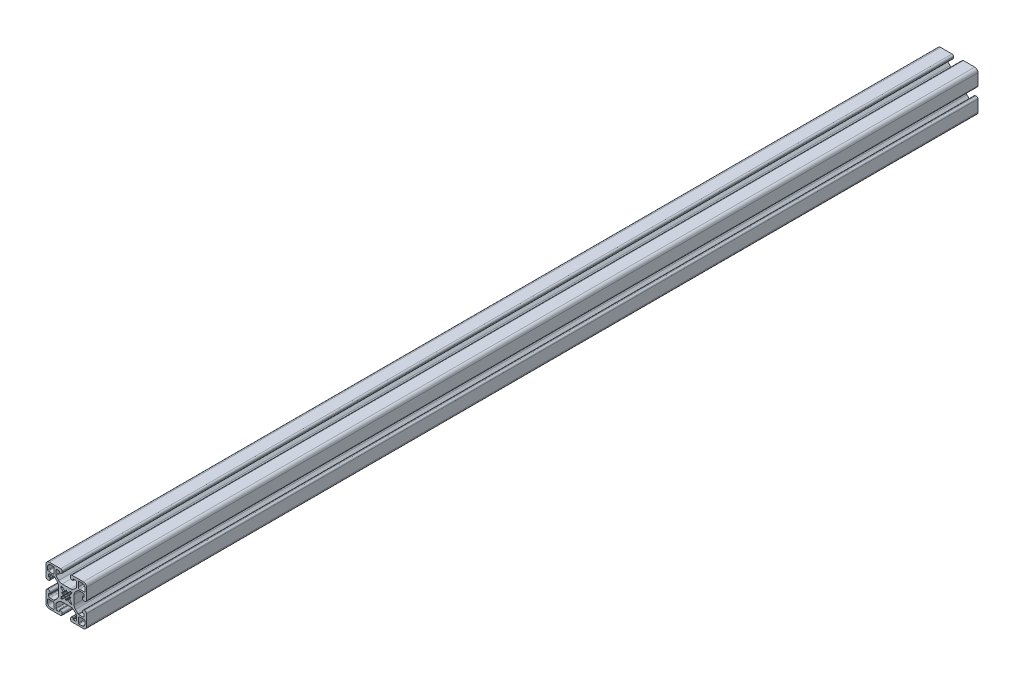
SolidWorks part; units mm, degrees
other "Extrude1"
material "6105-T5 Aluminum"
ref_plane "Front Plane" through (0, 0, 0) normal (0, 0, 1) x (1, 0, 0)
ref_plane "Top Plane" through (0, 0, 0) normal (0, 1, 0) x (1, 0, 0)
ref_plane "Right Plane" through (0, 0, 0) normal (1, 0, 0) x (0, 0, -1)
sketch "Sketch1" plane through (0, 0, 0) normal (0, 0, 1) x (1, 0, 0)
  line L0 (12.4898, -18.345) -> (15.545, -18.345)
  line L1 (11.8598, -13.1298) -> (11.8598, -17.715)
  line L2 (17.715, -11.8598) -> (13.1298, -11.8598)
  line L3 (18.345, -15.545) -> (18.345, -12.4898)
  line L4 (-18.345, -12.4898) -> (-18.345, -15.545)
  line L5 (-13.1298, -11.8598) -> (-17.715, -11.8598)
  line L6 (-11.8598, -17.715) -> (-11.8598, -13.1298)
  line L7 (-15.545, -18.345) -> (-12.4898, -18.345)
  line L8 (18.345, 12.4898) -> (18.345, 15.545)
  line L9 (13.1298, 11.8598) -> (17.715, 11.8598)
  line L10 (11.8598, 17.715) -> (11.8598, 13.1298)
  line L11 (15.545, 18.345) -> (12.4898, 18.345)
  line L12 (-12.4898, 18.345) -> (-15.545, 18.345)
  line L13 (-11.8598, 13.1298) -> (-11.8598, 17.715)
  line L14 (-17.715, 11.8598) -> (-13.1298, 11.8598)
  line L15 (-18.345, 15.545) -> (-18.345, 12.4898)
  line L16 (-5.63, 20) -> (-16.83, 20)
  line L17 (-20, 16.83) -> (-20, 5.63)
  line L18 (-18.43, 4.06) -> (-17.57, 4.06)
  line L19 (-16, 5.63) -> (-16, 6.605)
  line L20 (-16.25, 6.855) -> (-17.25, 6.855)
  line L21 (-17.5, 7.105) -> (-17.5, 9.015)
  line L22 (-16.23, 10.285) -> (-12.2162, 10.285)
  line L23 (-11.5869, 10.0243) -> (-9.0762, 7.5137)
  line L24 (-7.685, 4.1549) -> (-7.685, -4.1549)
  line L25 (-9.0762, -7.5137) -> (-11.5869, -10.0243)
  line L26 (-12.2162, -10.285) -> (-16.23, -10.285)
  line L27 (-17.5, -9.015) -> (-17.5, -7.105)
  line L28 (-17.25, -6.855) -> (-16.25, -6.855)
  line L29 (-16, -6.605) -> (-16, -5.63)
  line L30 (-17.57, -4.06) -> (-18.43, -4.06)
  line L31 (-20, -5.63) -> (-20, -16.83)
  line L32 (-16.83, -20) -> (-5.63, -20)
  line L33 (-4.06, -18.43) -> (-4.06, -17.57)
  line L34 (-5.63, -16) -> (-6.605, -16)
  line L35 (-6.855, -16.25) -> (-6.855, -17.25)
  line L36 (-7.105, -17.5) -> (-9.015, -17.5)
  line L37 (-10.285, -16.23) -> (-10.285, -12.2162)
  line L38 (-10.0243, -11.5869) -> (-7.5137, -9.0762)
  line L39 (-4.1549, -7.685) -> (4.1549, -7.685)
  line L40 (7.5137, -9.0762) -> (10.0243, -11.5869)
  line L41 (10.285, -12.2162) -> (10.285, -16.23)
  line L42 (9.015, -17.5) -> (7.105, -17.5)
  line L43 (6.855, -17.25) -> (6.855, -16.25)
  line L44 (6.605, -16) -> (5.63, -16)
  line L45 (4.06, -17.57) -> (4.06, -18.43)
  line L46 (5.63, -20) -> (16.83, -20)
  line L47 (20, -16.83) -> (20, -5.63)
  line L48 (18.43, -4.06) -> (17.57, -4.06)
  line L49 (16, -5.63) -> (16, -6.605)
  line L50 (16.25, -6.855) -> (17.25, -6.855)
  line L51 (17.5, -7.105) -> (17.5, -9.015)
  line L52 (16.23, -10.285) -> (12.2162, -10.285)
  line L53 (11.5869, -10.0243) -> (9.0762, -7.5137)
  line L54 (7.685, -4.1549) -> (7.685, 4.1549)
  line L55 (9.0762, 7.5137) -> (11.5869, 10.0243)
  line L56 (12.2162, 10.285) -> (16.23, 10.285)
  line L57 (17.5, 9.015) -> (17.5, 7.105)
  line L58 (17.25, 6.855) -> (16.25, 6.855)
  line L59 (16, 6.605) -> (16, 5.63)
  line L60 (17.57, 4.06) -> (18.43, 4.06)
  line L61 (20, 5.63) -> (20, 16.83)
  line L62 (16.83, 20) -> (5.63, 20)
  line L63 (4.06, 18.43) -> (4.06, 17.57)
  line L64 (5.63, 16) -> (6.605, 16)
  line L65 (6.855, 16.25) -> (6.855, 17.25)
  line L66 (7.105, 17.5) -> (9.015, 17.5)
  line L67 (10.285, 16.23) -> (10.285, 12.2162)
  line L68 (10.0243, 11.5869) -> (7.5137, 9.0762)
  line L69 (4.1549, 7.685) -> (-4.1549, 7.685)
  line L70 (-7.5137, 9.0762) -> (-10.0243, 11.5869)
  line L71 (-10.285, 12.2162) -> (-10.285, 16.23)
  line L72 (-9.015, 17.5) -> (-7.105, 17.5)
  line L73 (-6.855, 17.25) -> (-6.855, 16.25)
  line L74 (-6.605, 16) -> (-5.63, 16)
  line L75 (-4.06, 17.57) -> (-4.06, 18.43)
  line L76 (-4.8481, -5.4393) -> (-3.712, -5.1263)
  line L77 (-3.712, -5.1263) -> (-1.5907, -3.0049)
  line L78 (-0.625, -3.3421) -> (-0.4923, -4.0876)
  line L79 (0.4923, -4.0876) -> (0.625, -3.3421)
  line L80 (1.5907, -3.0049) -> (3.712, -5.1263)
  line L81 (3.712, -5.1263) -> (4.8481, -5.4393)
  line L82 (5.4393, -4.8481) -> (5.1263, -3.712)
  line L83 (5.1263, -3.712) -> (3.0049, -1.5907)
  line L84 (3.3421, -0.625) -> (4.0876, -0.4923)
  line L85 (4.0876, 0.4923) -> (3.3421, 0.625)
  line L86 (3.0049, 1.5907) -> (5.1263, 3.712)
  line L87 (5.1263, 3.712) -> (5.4393, 4.8481)
  line L88 (4.8481, 5.4393) -> (3.712, 5.1263)
  line L89 (3.712, 5.1263) -> (1.5907, 3.0049)
  line L90 (0.625, 3.3421) -> (0.4923, 4.0876)
  line L91 (-0.4923, 4.0876) -> (-0.625, 3.3421)
  line L92 (-1.5907, 3.0049) -> (-3.712, 5.1263)
  line L93 (-3.712, 5.1263) -> (-4.8481, 5.4393)
  line L94 (-5.4393, 4.8481) -> (-5.1263, 3.712)
  line L95 (-5.1263, 3.712) -> (-3.0049, 1.5907)
  line L96 (-3.3421, 0.625) -> (-4.0876, 0.4923)
  line L97 (-4.0876, -0.4923) -> (-3.3421, -0.625)
  line L98 (-3.0049, -1.5907) -> (-5.1263, -3.712)
  line L99 (-5.1263, -3.712) -> (-5.4393, -4.8481)
  arc A0 (15.545, -18.345) -> (18.345, -15.545) centre (15.545, -15.545) ccw
  arc A1 (11.8598, -17.715) -> (12.4898, -18.345) centre (12.4898, -17.715) ccw
  arc A2 (13.1298, -11.8598) -> (11.8598, -13.1298) centre (13.1298, -13.1298) ccw
  arc A3 (18.345, -12.4898) -> (17.715, -11.8598) centre (17.715, -12.4898) ccw
  arc A4 (-18.345, -15.545) -> (-15.545, -18.345) centre (-15.545, -15.545) ccw
  arc A5 (-17.715, -11.8598) -> (-18.345, -12.4898) centre (-17.715, -12.4898) ccw
  arc A6 (-11.8598, -13.1298) -> (-13.1298, -11.8598) centre (-13.1298, -13.1298) ccw
  arc A7 (-12.4898, -18.345) -> (-11.8598, -17.715) centre (-12.4898, -17.715) ccw
  arc A8 (18.345, 15.545) -> (15.545, 18.345) centre (15.545, 15.545) ccw
  arc A9 (17.715, 11.8598) -> (18.345, 12.4898) centre (17.715, 12.4898) ccw
  arc A10 (11.8598, 13.1298) -> (13.1298, 11.8598) centre (13.1298, 13.1298) ccw
  arc A11 (12.4898, 18.345) -> (11.8598, 17.715) centre (12.4898, 17.715) ccw
  arc A12 (-15.545, 18.345) -> (-18.345, 15.545) centre (-15.545, 15.545) ccw
  arc A13 (-11.8598, 17.715) -> (-12.4898, 18.345) centre (-12.4898, 17.715) ccw
  arc A14 (-13.1298, 11.8598) -> (-11.8598, 13.1298) centre (-13.1298, 13.1298) ccw
  arc A15 (-18.345, 12.4898) -> (-17.715, 11.8598) centre (-17.715, 12.4898) ccw
  arc A16 (-4.06, 18.43) -> (-5.63, 20) centre (-5.63, 18.43) ccw
  arc A17 (-16.83, 20) -> (-20, 16.83) centre (-16.83, 16.83) ccw
  arc A18 (-20, 5.63) -> (-18.43, 4.06) centre (-18.43, 5.63) ccw
  arc A19 (-17.57, 4.06) -> (-16, 5.63) centre (-17.57, 5.63) ccw
  arc A20 (-16, 6.605) -> (-16.25, 6.855) centre (-16.25, 6.605) ccw
  arc A21 (-17.5, 7.105) -> (-17.25, 6.855) centre (-17.25, 7.105) ccw
  arc A22 (-16.23, 10.285) -> (-17.5, 9.015) centre (-16.23, 9.015) ccw
  arc A23 (-11.5869, 10.0243) -> (-12.2162, 10.285) centre (-12.2162, 9.395) ccw
  arc A24 (-7.685, 4.1549) -> (-9.0762, 7.5137) centre (-12.435, 4.1549) ccw
  arc A25 (-9.0762, -7.5137) -> (-7.685, -4.1549) centre (-12.435, -4.1549) ccw
  arc A26 (-12.2162, -10.285) -> (-11.5869, -10.0243) centre (-12.2162, -9.395) ccw
  arc A27 (-17.5, -9.015) -> (-16.23, -10.285) centre (-16.23, -9.015) ccw
  arc A28 (-17.25, -6.855) -> (-17.5, -7.105) centre (-17.25, -7.105) ccw
  arc A29 (-16.25, -6.855) -> (-16, -6.605) centre (-16.25, -6.605) ccw
  arc A30 (-16, -5.63) -> (-17.57, -4.06) centre (-17.57, -5.63) ccw
  arc A31 (-18.43, -4.06) -> (-20, -5.63) centre (-18.43, -5.63) ccw
  arc A32 (-20, -16.83) -> (-16.83, -20) centre (-16.83, -16.83) ccw
  arc A33 (-5.63, -20) -> (-4.06, -18.43) centre (-5.63, -18.43) ccw
  arc A34 (-4.06, -17.57) -> (-5.63, -16) centre (-5.63, -17.57) ccw
  arc A35 (-6.605, -16) -> (-6.855, -16.25) centre (-6.605, -16.25) ccw
  arc A36 (-7.105, -17.5) -> (-6.855, -17.25) centre (-7.105, -17.25) ccw
  arc A37 (-10.285, -16.23) -> (-9.015, -17.5) centre (-9.015, -16.23) ccw
  arc A38 (-10.0243, -11.5869) -> (-10.285, -12.2162) centre (-9.395, -12.2162) ccw
  arc A39 (-4.1549, -7.685) -> (-7.5137, -9.0762) centre (-4.1549, -12.435) ccw
  arc A40 (7.5137, -9.0762) -> (4.1549, -7.685) centre (4.1549, -12.435) ccw
  arc A41 (10.285, -12.2162) -> (10.0243, -11.5869) centre (9.395, -12.2162) ccw
  arc A42 (9.015, -17.5) -> (10.285, -16.23) centre (9.015, -16.23) ccw
  arc A43 (6.855, -17.25) -> (7.105, -17.5) centre (7.105, -17.25) ccw
  arc A44 (6.855, -16.25) -> (6.605, -16) centre (6.605, -16.25) ccw
  arc A45 (5.63, -16) -> (4.06, -17.57) centre (5.63, -17.57) ccw
  arc A46 (4.06, -18.43) -> (5.63, -20) centre (5.63, -18.43) ccw
  arc A47 (16.83, -20) -> (20, -16.83) centre (16.83, -16.83) ccw
  arc A48 (20, -5.63) -> (18.43, -4.06) centre (18.43, -5.63) ccw
  arc A49 (17.57, -4.06) -> (16, -5.63) centre (17.57, -5.63) ccw
  arc A50 (16, -6.605) -> (16.25, -6.855) centre (16.25, -6.605) ccw
  arc A51 (17.5, -7.105) -> (17.25, -6.855) centre (17.25, -7.105) ccw
  arc A52 (16.23, -10.285) -> (17.5, -9.015) centre (16.23, -9.015) ccw
  arc A53 (11.5869, -10.0243) -> (12.2162, -10.285) centre (12.2162, -9.395) ccw
  arc A54 (7.685, -4.1549) -> (9.0762, -7.5137) centre (12.435, -4.1549) ccw
  arc A55 (9.0762, 7.5137) -> (7.685, 4.1549) centre (12.435, 4.1549) ccw
  arc A56 (12.2162, 10.285) -> (11.5869, 10.0243) centre (12.2162, 9.395) ccw
  arc A57 (17.5, 9.015) -> (16.23, 10.285) centre (16.23, 9.015) ccw
  arc A58 (17.25, 6.855) -> (17.5, 7.105) centre (17.25, 7.105) ccw
  arc A59 (16.25, 6.855) -> (16, 6.605) centre (16.25, 6.605) ccw
  arc A60 (16, 5.63) -> (17.57, 4.06) centre (17.57, 5.63) ccw
  arc A61 (18.43, 4.06) -> (20, 5.63) centre (18.43, 5.63) ccw
  arc A62 (20, 16.83) -> (16.83, 20) centre (16.83, 16.83) ccw
  arc A63 (5.63, 20) -> (4.06, 18.43) centre (5.63, 18.43) ccw
  arc A64 (4.06, 17.57) -> (5.63, 16) centre (5.63, 17.57) ccw
  arc A65 (6.605, 16) -> (6.855, 16.25) centre (6.605, 16.25) ccw
  arc A66 (7.105, 17.5) -> (6.855, 17.25) centre (7.105, 17.25) ccw
  arc A67 (10.285, 16.23) -> (9.015, 17.5) centre (9.015, 16.23) ccw
  arc A68 (10.0243, 11.5869) -> (10.285, 12.2162) centre (9.395, 12.2162) ccw
  arc A69 (4.1549, 7.685) -> (7.5137, 9.0762) centre (4.1549, 12.435) ccw
  arc A70 (-7.5137, 9.0762) -> (-4.1549, 7.685) centre (-4.1549, 12.435) ccw
  arc A71 (-10.285, 12.2162) -> (-10.0243, 11.5869) centre (-9.395, 12.2162) ccw
  arc A72 (-9.015, 17.5) -> (-10.285, 16.23) centre (-9.015, 16.23) ccw
  arc A73 (-6.855, 17.25) -> (-7.105, 17.5) centre (-7.105, 17.25) ccw
  arc A74 (-6.855, 16.25) -> (-6.605, 16) centre (-6.605, 16.25) ccw
  arc A75 (-5.63, 16) -> (-4.06, 17.57) centre (-5.63, 17.57) ccw
  arc A76 (-1.5907, -3.0049) -> (-0.625, -3.3421) centre (0, 0) ccw
  arc A77 (-0.4923, -4.0876) -> (0.4923, -4.0876) centre (0, -4) ccw
  arc A78 (0.625, -3.3421) -> (1.5907, -3.0049) centre (0, 0) ccw
  arc A79 (4.8481, -5.4393) -> (5.4393, -4.8481) centre (4.9497, -4.9497) ccw
  arc A80 (3.0049, -1.5907) -> (3.3421, -0.625) centre (0, 0) ccw
  arc A81 (4.0876, -0.4923) -> (4.0876, 0.4923) centre (4, 0) ccw
  arc A82 (3.3421, 0.625) -> (3.0049, 1.5907) centre (0, 0) ccw
  arc A83 (5.4393, 4.8481) -> (4.8481, 5.4393) centre (4.9497, 4.9497) ccw
  arc A84 (1.5907, 3.0049) -> (0.625, 3.3421) centre (0, 0) ccw
  arc A85 (0.4923, 4.0876) -> (-0.4923, 4.0876) centre (0, 4) ccw
  arc A86 (-0.625, 3.3421) -> (-1.5907, 3.0049) centre (0, 0) ccw
  arc A87 (-4.8481, 5.4393) -> (-5.4393, 4.8481) centre (-4.9497, 4.9497) ccw
  arc A88 (-3.0049, 1.5907) -> (-3.3421, 0.625) centre (0, 0) ccw
  arc A89 (-4.0876, 0.4923) -> (-4.0876, -0.4923) centre (-4, 0) ccw
  arc A90 (-3.3421, -0.625) -> (-3.0049, -1.5907) centre (0, 0) ccw
  arc A91 (-5.4393, -4.8481) -> (-4.8481, -5.4393) centre (-4.9497, -4.9497) ccw
extrude "Extrude1" add sketch "Sketch1" against normal blind 880
equation "\"0.400.00mm\"=1400"
